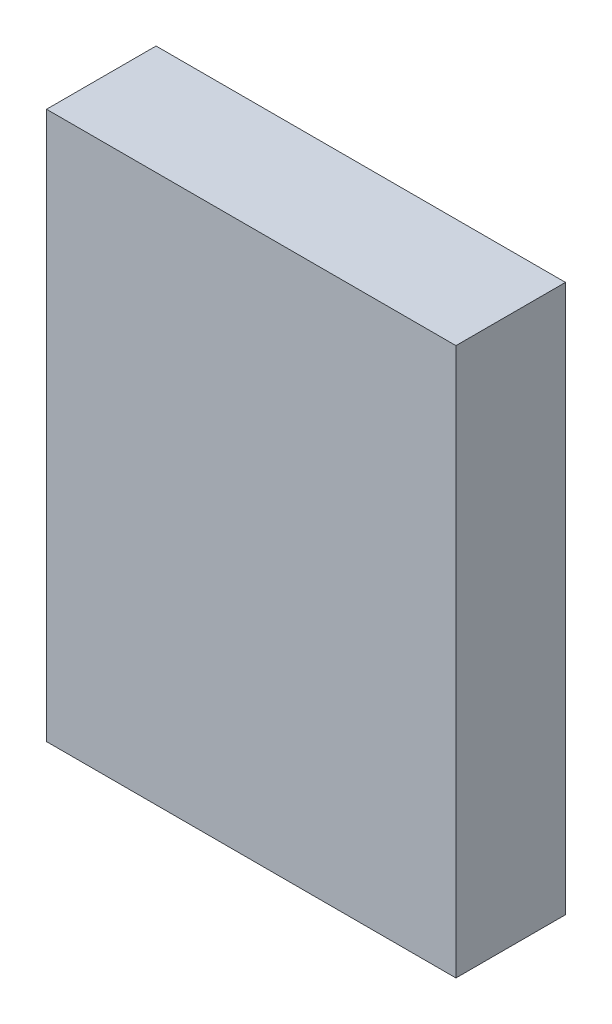
SolidWorks part; units mm, degrees
ref_plane "Спереди" through (0, 0, 0) normal (0, 0, 1) x (1, 0, 0)
ref_plane "Сверху" through (0, 0, 0) normal (0, 1, 0) x (1, 0, 0)
ref_plane "Справа" through (0, 0, 0) normal (1, 0, 0) x (0, 0, -1)
sketch "Эскиз5" plane through (0, 0, 0) normal (0, 0, 1) x (1, 0, 0)
  line L1 (-18.689, -25) -> (18.689, -25)
  line L2 (-18.689, -25) -> (-18.689, 25)
  line L3 (-18.689, 25) -> (18.689, 25)
  line L4 (18.689, -25) -> (18.689, 25)
  line L5 (-18.689, -25) -> (18.689, 25) construction
  line L6 (-18.689, 25) -> (18.689, -25) construction
  point P0 (0, 0)
extrude "Бобышка-Вытянуть2" add sketch "Эскиз5" along normal blind 10 contours L2 L3 L4 L1
sketch "ангренажный мост" plane through (0, 0, 10) normal (0, 0, 1) x (1, 0, 0)
  line L0 (-7.8996, -16.334) -> (-3.787, -11.9127)
  line L1 (1.1069, -9.3047) -> (3.4546, -11.6681)
  line L2 (3.9401, -11.9208) -> (8.2701, -12.6678)
  line L3 (9.4343, -11.4735) -> (9.7159, -10.401)
  line L4 (10.2173, -9.77) -> (11.3033, -9.1983)
  line L5 (11.6059, -14.0549) -> (8.4903, -14.3541)
  line L6 (8.3946, -14.3053) -> (-2.7438, -15.3749)
  line L7 (-2.7438, -15.3749) -> (-5.959, -18.794)
  line L8 (-5.9854, -20.5913) -> (-5.6833, -22.7215)
  line L9 (-5.8831, -23.4496) -> (-6.3288, -24.0048)
  line L10 (-11.3637, -19.8827) -> (-8.0539, -16.3245)
  line L11 (9.3569, -11.7683) -> (9.2937, -12.0094)
  line L12 (9.3569, -0.7683) -> (9.2937, -1.0094)
  line L13 (9.4343, -0.4735) -> (9.7159, 0.599)
  line L14 (10.2173, 1.23) -> (11.3033, 1.8017)
  line L15 (11.6059, -3.0549) -> (8.4903, -3.3541)
  line L16 (8.3946, -3.3053) -> (-2.7438, -4.3749)
  line L17 (-2.7438, -4.3749) -> (-5.959, -7.794)
  line L18 (-5.9854, -9.5913) -> (-5.6833, -11.7215)
  line L19 (-5.8831, -12.4496) -> (-6.3288, -13.0048)
  line L20 (-11.3637, -8.8827) -> (-8.0539, -5.3245)
  line L21 (-7.8996, -5.334) -> (-3.787, -0.9127)
  line L22 (1.1069, 1.6953) -> (3.4546, -0.6681)
  line L23 (3.9401, -0.9208) -> (8.2701, -1.6678)
  line L24 (9.3569, 10.2317) -> (9.2937, 9.9906)
  line L25 (9.4343, 10.5265) -> (9.7159, 11.599)
  line L26 (10.2173, 12.23) -> (11.3033, 12.8017)
  line L27 (11.6059, 7.9451) -> (8.4903, 7.6459)
  line L28 (8.3946, 7.6947) -> (-2.7438, 6.6251)
  line L29 (-2.7438, 6.6251) -> (-5.959, 3.206)
  line L30 (-5.9854, 1.4087) -> (-5.6833, -0.7215)
  line L31 (-5.8831, -1.4496) -> (-6.3288, -2.0048)
  line L32 (-11.3637, 2.1173) -> (-8.0539, 5.6755)
  line L33 (-7.8996, 5.666) -> (-3.787, 10.0873)
  line L34 (1.1069, 12.6953) -> (3.4546, 10.3319)
  line L35 (3.9401, 10.0792) -> (8.2701, 9.3322)
  line L36 (9.3569, 21.2317) -> (9.2937, 20.9906)
  line L37 (9.4343, 21.5265) -> (9.7159, 22.599)
  line L38 (10.2173, 23.23) -> (11.3033, 23.8017)
  line L39 (11.6059, 18.9451) -> (8.4903, 18.6459)
  line L40 (8.3946, 18.6947) -> (-2.7438, 17.6251)
  line L41 (-2.7438, 17.6251) -> (-5.959, 14.206)
  line L42 (-5.9854, 12.4087) -> (-5.6833, 10.2785)
  line L43 (-5.8831, 9.5504) -> (-6.3288, 8.9952)
  line L44 (-11.3637, 13.1173) -> (-8.0539, 16.6755)
  line L45 (-7.8996, 16.666) -> (-3.787, 21.0873)
  line L46 (1.1069, 23.6953) -> (3.4546, 21.3319)
  line L47 (3.9401, 21.0792) -> (8.2701, 20.3322)
  arc A17 (-11.3637, -19.8827) -> (-9.4971, -21.9436) centre (-1.0368, -12.4049) ccw
  arc A18 (-8.0539, -16.3245) -> (-7.8996, -16.334) centre (-7.9728, -16.2659) ccw
  arc A19 (-3.787, -11.9127) -> (-1.6906, -11.5403) centre (-3.7358, -6.1129) ccw
  arc A20 (9.1133, -1.3586) -> (9.2937, -1.0094) centre (8.4232, -0.7809) ccw
  arc A21 (-1.2128, -11.3353) -> (1.1069, -9.3047) centre (-3.7358, -6.1129) ccw
  arc A22 (3.4546, -11.6681) -> (3.9401, -11.9208) centre (4.0932, -11.0339) ccw
  arc A23 (8.2701, -12.6678) -> (8.9443, -12.5146) centre (8.4232, -11.7809) ccw
  arc A24 (10.2173, 1.23) -> (9.7159, 0.599) centre (10.6832, 0.3451) ccw
  arc A25 (10.2173, -9.77) -> (9.7159, -10.401) centre (10.6832, -10.6549) ccw
  arc A26 (11.6059, -14.0549) -> (11.3033, -9.1983) centre (-1.0368, -12.4049) ccw
  arc A27 (8.4903, -14.3541) -> (8.3946, -14.3053) centre (8.4042, -14.4049) ccw
  arc A28 (-5.959, -18.794) -> (-5.9854, -20.5913) centre (-0.2428, -19.7769) ccw
  arc A29 (-5.8831, -23.4496) -> (-5.6833, -22.7215) centre (-6.6238, -22.8549) ccw
  arc A30 (-8.0552, -23.0493) -> (-6.3288, -24.0048) centre (-1.0368, -12.4049) ccw
  arc A31 (-8.0552, -23.0493) -> (-9.4971, -21.9436) centre (-8.5218, -22.1649) ccw
  arc A44 (11.6059, -3.0549) -> (11.3033, 1.8017) centre (-1.0368, -1.4049) ccw
  arc A51 (9.1133, -12.3586) -> (9.2937, -12.0094) centre (8.4232, -11.7809) ccw
  arc A52 (8.4903, -3.3541) -> (8.3946, -3.3053) centre (8.4042, -3.4049) ccw
  arc A53 (-5.959, -7.794) -> (-5.9854, -9.5913) centre (-0.2428, -8.7769) ccw
  arc A54 (-5.8831, -12.4496) -> (-5.6833, -11.7215) centre (-6.6238, -11.8549) ccw
  arc A55 (-8.0552, -12.0493) -> (-6.3288, -13.0048) centre (-1.0368, -1.4049) ccw
  arc A56 (-8.0552, -12.0493) -> (-9.4971, -10.9436) centre (-8.5218, -11.1649) ccw
  arc A57 (-11.3637, -8.8827) -> (-9.4971, -10.9436) centre (-1.0368, -1.4049) ccw
  arc A58 (-8.0539, -5.3245) -> (-7.8996, -5.334) centre (-7.9728, -5.2659) ccw
  arc A59 (-3.787, -0.9127) -> (-1.6906, -0.5403) centre (-3.7358, 4.8871) ccw
  arc A60 (-1.2128, -0.3353) -> (1.1069, 1.6953) centre (-3.7358, 4.8871) ccw
  arc A61 (3.4546, -0.6681) -> (3.9401, -0.9208) centre (4.0932, -0.0339) ccw
  arc A62 (8.2701, -1.6678) -> (8.9443, -1.5146) centre (8.4232, -0.7809) ccw
  arc A63 (9.1133, 9.6414) -> (9.2937, 9.9906) centre (8.4232, 10.2191) ccw
  arc A64 (10.2173, 12.23) -> (9.7159, 11.599) centre (10.6832, 11.3451) ccw
  arc A65 (11.6059, 7.9451) -> (11.3033, 12.8017) centre (-1.0368, 9.5951) ccw
  arc A66 (8.4903, 7.6459) -> (8.3946, 7.6947) centre (8.4042, 7.5951) ccw
  arc A67 (-5.959, 3.206) -> (-5.9854, 1.4087) centre (-0.2428, 2.2231) ccw
  arc A68 (-5.8831, -1.4496) -> (-5.6833, -0.7215) centre (-6.6238, -0.8549) ccw
  arc A69 (-8.0552, -1.0493) -> (-6.3288, -2.0048) centre (-1.0368, 9.5951) ccw
  arc A70 (-8.0552, -1.0493) -> (-9.4971, 0.0564) centre (-8.5218, -0.1649) ccw
  arc A71 (-11.3637, 2.1173) -> (-9.4971, 0.0564) centre (-1.0368, 9.5951) ccw
  arc A72 (-8.0539, 5.6755) -> (-7.8996, 5.666) centre (-7.9728, 5.7341) ccw
  arc A73 (-3.787, 10.0873) -> (-1.6906, 10.4597) centre (-3.7358, 15.8871) ccw
  arc A74 (-1.2128, 10.6647) -> (1.1069, 12.6953) centre (-3.7358, 15.8871) ccw
  arc A75 (3.4546, 10.3319) -> (3.9401, 10.0792) centre (4.0932, 10.9661) ccw
  arc A76 (8.2701, 9.3322) -> (8.9443, 9.4854) centre (8.4232, 10.2191) ccw
  arc A77 (9.1133, 20.6414) -> (9.2937, 20.9906) centre (8.4232, 21.2191) ccw
  arc A78 (10.2173, 23.23) -> (9.7159, 22.599) centre (10.6832, 22.3451) ccw
  arc A79 (11.6059, 18.9451) -> (11.3033, 23.8017) centre (-1.0368, 20.5951) ccw
  arc A80 (8.4903, 18.6459) -> (8.3946, 18.6947) centre (8.4042, 18.5951) ccw
  arc A81 (-5.959, 14.206) -> (-5.9854, 12.4087) centre (-0.2428, 13.2231) ccw
  arc A82 (-5.8831, 9.5504) -> (-5.6833, 10.2785) centre (-6.6238, 10.1451) ccw
  arc A83 (-8.0552, 9.9507) -> (-6.3288, 8.9952) centre (-1.0368, 20.5951) ccw
  arc A84 (-8.0552, 9.9507) -> (-9.4971, 11.0564) centre (-8.5218, 10.8351) ccw
  arc A85 (-11.3637, 13.1173) -> (-9.4971, 11.0564) centre (-1.0368, 20.5951) ccw
  arc A86 (-8.0539, 16.6755) -> (-7.8996, 16.666) centre (-7.9728, 16.7341) ccw
  arc A87 (-3.787, 21.0873) -> (-1.6906, 21.4597) centre (-3.7358, 26.8871) ccw
  arc A88 (-1.2128, 21.6647) -> (1.1069, 23.6953) centre (-3.7358, 26.8871) ccw
  arc A89 (3.4546, 21.3319) -> (3.9401, 21.0792) centre (4.0932, 21.9661) ccw
  arc A90 (8.2701, 20.3322) -> (8.9443, 20.4854) centre (8.4232, 21.2191) ccw
  spline S0 degree 3 poles (9.4343, -0.4735) (9.4089, -0.5703) (9.3832, -0.6682) (9.3569, -0.7683) knots 0 0 0 0 1 1 1 1
  spline S1 degree 3 poles (-1.6906, -11.5403) (-1.6123, -11.5108) (-1.5305, -11.478) (-1.3682, -11.4084) (-1.2881, -11.3718) (-1.2128, -11.3353) knots 0 0 0 0 0.5 0.5 1 1 1 1
  spline S2 degree 3 poles (-1.6906, -0.5403) (-1.6123, -0.5108) (-1.5305, -0.478) (-1.3682, -0.4084) (-1.2881, -0.3718) (-1.2128, -0.3353) knots 0 0 0 0 0.5 0.5 1 1 1 1
  spline S3 degree 3 poles (9.1133, -1.3586) (9.0621, -1.4197) (9.0057, -1.471) (8.9443, -1.5146) knots 0 0 0 0 1 1 1 1
  spline S4 degree 3 poles (9.4343, 10.5265) (9.4089, 10.4297) (9.3832, 10.3318) (9.3569, 10.2317) knots 0 0 0 0 1 1 1 1
  spline S5 degree 3 poles (9.4343, -11.4735) (9.4089, -11.5703) (9.3832, -11.6682) (9.3569, -11.7683) knots 0 0 0 0 1 1 1 1
  spline S6 degree 3 poles (9.1133, -12.3586) (9.0621, -12.4197) (9.0057, -12.471) (8.9443, -12.5146) knots 0 0 0 0 1 1 1 1
  spline S7 degree 3 poles (-1.6906, 10.4597) (-1.6123, 10.4892) (-1.5305, 10.522) (-1.3682, 10.5916) (-1.2881, 10.6282) (-1.2128, 10.6647) knots 0 0 0 0 0.5 0.5 1 1 1 1
  spline S8 degree 3 poles (9.1133, 9.6414) (9.0621, 9.5803) (9.0057, 9.529) (8.9443, 9.4854) knots 0 0 0 0 1 1 1 1
  spline S9 degree 3 poles (9.4343, 21.5265) (9.4089, 21.4297) (9.3832, 21.3318) (9.3569, 21.2317) knots 0 0 0 0 1 1 1 1
  spline S10 degree 3 poles (-1.6906, 21.4597) (-1.6123, 21.4892) (-1.5305, 21.522) (-1.3682, 21.5916) (-1.2881, 21.6282) (-1.2128, 21.6647) knots 0 0 0 0 0.5 0.5 1 1 1 1
  spline S11 degree 3 poles (9.1133, 20.6414) (9.0621, 20.5803) (9.0057, 20.529) (8.9443, 20.4854) knots 0 0 0 0 1 1 1 1
  dimension "D1" = 4
sketch "под штифты и углы" plane through (0, 0, 10) normal (0, 0, 1) x (1, 0, 0)
  circle A0 centre (10.6832, -10.6549) radius 1
  circle A1 centre (-6.6238, -22.8549) radius 1
  circle A4 centre (-9.4971, -21.9436) radius 1
  circle A5 centre (-8.0552, -23.0493) radius 1
  circle A6 centre (9.7735, -9.5605) radius 1
  circle A7 centre (11.0975, -8.9025) radius 1
  circle A8 centre (11.8685, -14.5114) radius 1
  circle A9 centre (9.7735, 1.4395) radius 1
  circle A10 centre (11.0975, 2.0975) radius 1
  circle A11 centre (10.6832, 0.3451) radius 1
  circle A12 centre (11.8685, -3.5114) radius 1
  circle A13 centre (-9.4971, -10.9436) radius 1
  circle A14 centre (-8.0552, -12.0493) radius 1
  circle A15 centre (-6.6238, -11.8549) radius 1
  circle A16 centre (9.7735, 12.4395) radius 1
  circle A17 centre (11.0975, 13.0975) radius 1
  circle A18 centre (10.6832, 11.3451) radius 1
  circle A19 centre (11.8685, 7.4886) radius 1
  circle A20 centre (-9.4971, 0.0564) radius 1
  circle A21 centre (-8.0552, -1.0493) radius 1
  circle A22 centre (-6.6238, -0.8549) radius 1
  circle A23 centre (9.7735, 23.4395) radius 1
  circle A24 centre (11.0975, 24.0975) radius 1
  circle A25 centre (10.6832, 22.3451) radius 1
  circle A26 centre (11.8685, 18.4886) radius 1
  circle A27 centre (-9.4971, 11.0564) radius 1
  circle A28 centre (-8.0552, 9.9507) radius 1
  circle A29 centre (-6.6238, 10.1451) radius 1
  dimension "D1" = 4
sketch "сЪем" plane through (0, 0, 10) normal (0, 0, 1) x (1, 0, 0)
  line L0 (0, -32.2096) -> (0, 32.2096) construction
  line L1 (-1, -32.2096) -> (-1, 32.2096)
  line L2 (1, -32.2096) -> (1, 32.2096)
  arc A0 (-1, -32.2096) -> (1, -32.2096) centre (0, -32.2096) ccw
  arc A1 (1, 32.2096) -> (-1, 32.2096) centre (0, 32.2096) ccw
  point P2 (0, 0)
sketch "перлаж" plane through (0, 0, 10) normal (0, 0, 1) x (1, 0, 0)
  circle A0 centre (-10.5945, -20.0559) radius 1
  circle A1 centre (-9.4734, -20.898) radius 1
  circle A3 centre (-7.2312, -22.5823) radius 1
  circle A4 centre (-6.1101, -23.4244) radius 1
  circle A11 centre (-7.464, -20.763) radius 1
  circle A12 centre (-6.3429, -21.6052) radius 1
  circle A19 centre (-7.6968, -18.9438) radius 1
  circle A20 centre (-6.5757, -19.7859) radius 1
  circle A28 centre (-6.8085, -17.9666) radius 1
  circle A29 centre (-5.6874, -18.8088) radius 1
  circle A37 centre (-5.9202, -16.9895) radius 1
  circle A38 centre (-4.799, -17.8316) radius 1
  circle A46 centre (-5.0318, -16.0124) radius 1
  circle A47 centre (-3.9107, -16.8545) radius 1
  circle A55 centre (-4.1435, -15.0352) radius 1
  circle A56 centre (-3.0224, -15.8774) radius 1
  circle A64 centre (-3.2552, -14.0581) radius 1
  circle A65 centre (-2.1341, -14.9002) radius 1
  circle A73 centre (-2.3669, -13.081) radius 1
  circle A74 centre (-1.2458, -13.9231) radius 1
  circle A75 centre (-0.1247, -14.7652) radius 1
  circle A82 centre (-1.4786, -12.1038) radius 1
  circle A83 centre (-0.3575, -12.946) radius 1
  circle A84 centre (0.7636, -13.7881) radius 1
  circle A85 centre (1.8847, -14.6302) radius 1
  circle A91 centre (-0.5903, -11.1267) radius 1
  circle A92 centre (0.5308, -11.9688) radius 1
  circle A93 centre (1.6519, -12.8109) radius 1
  circle A94 centre (2.7731, -13.6531) radius 1
  circle A95 centre (3.8942, -14.4952) radius 1
  circle A101 centre (1.4191, -10.9917) radius 1
  circle A102 centre (2.5403, -11.8338) radius 1
  circle A103 centre (3.6614, -12.6759) radius 1
  circle A104 centre (4.7825, -13.5181) radius 1
  circle A105 centre (5.9036, -14.3602) radius 1
  circle A112 centre (4.5497, -11.6988) radius 1
  circle A113 centre (5.6708, -12.5409) radius 1
  circle A114 centre (6.7919, -13.383) radius 1
  circle A115 centre (7.913, -14.2252) radius 1
  circle A123 centre (7.6802, -12.4059) radius 1
  circle A124 centre (8.8013, -13.248) radius 1
  circle A125 centre (9.9224, -14.0902) radius 1
  circle A143 centre (11.6991, -12.1359) radius 1
  circle A151 centre (11.4663, -10.3166) radius 1
  circle A163 centre (-9.7062, -19.0788) radius 1
  circle A164 centre (-8.8179, -18.1017) radius 1
  circle A165 centre (-7.9296, -17.1245) radius 1
  circle A166 centre (-7.0413, -16.1474) radius 1
  circle A167 centre (-6.153, -15.1703) radius 1
  circle A168 centre (-5.2646, -14.1931) radius 1
  circle A169 centre (-4.3763, -13.216) radius 1
  circle A170 centre (-3.488, -12.2389) radius 1
  circle A171 centre (-2.5997, -11.2617) radius 1
  circle A180 centre (-4.9889, -24.2665) radius 1
  circle A181 centre (-3.8678, -25.1087) radius 1
  circle A182 centre (-2.7467, -25.9508) radius 1
  circle A183 centre (-1.6256, -26.7929) radius 1
  circle A184 centre (-0.5045, -27.635) radius 1
  circle A185 centre (-4.1006, -23.2894) radius 1
  circle A186 centre (-2.9795, -24.1315) radius 1
  circle A187 centre (-1.8584, -24.9736) radius 1
  circle A188 centre (-0.7373, -25.8158) radius 1
  circle A189 centre (0.3838, -26.6579) radius 1
  circle A190 centre (-3.2123, -22.3123) radius 1
  circle A191 centre (-2.0912, -23.1544) radius 1
  circle A192 centre (-0.9701, -23.9965) radius 1
  circle A193 centre (0.151, -24.8386) radius 1
  circle A194 centre (1.2721, -25.6807) radius 1
  circle A195 centre (-3.4451, -20.493) radius 1
  circle A196 centre (-2.324, -21.3351) radius 1
  circle A197 centre (-1.2029, -22.1773) radius 1
  circle A198 centre (-0.0818, -23.0194) radius 1
  circle A199 centre (1.0393, -23.8615) radius 1
  circle A200 centre (2.1604, -24.7036) radius 1
  circle A201 centre (-0.3146, -21.2001) radius 1
  circle A202 centre (0.8065, -22.0422) radius 1
  circle A203 centre (1.9276, -22.8844) radius 1
  circle A204 centre (3.0487, -23.7265) radius 1
  circle A205 centre (1.6948, -21.0651) radius 1
  circle A206 centre (2.8159, -21.9072) radius 1
  circle A207 centre (3.9371, -22.7493) radius 1
  circle A208 centre (3.7043, -20.9301) radius 1
  circle A209 centre (-4.5662, -19.6509) radius 1
  circle A210 centre (-4.3334, -21.4701) radius 1
  circle A211 centre (0.5737, -20.223) radius 1
  circle A212 centre (0.3409, -18.4037) radius 1
  circle A213 centre (1.462, -19.2458) radius 1
  circle A214 centre (2.5831, -20.088) radius 1
  circle A215 centre (4.8254, -21.7722) radius 1
  circle A216 centre (0.1081, -16.5845) radius 1
  circle A217 centre (1.2292, -17.4266) radius 1
  circle A218 centre (2.3503, -18.2687) radius 1
  circle A219 centre (3.4715, -19.1108) radius 1
  circle A220 centre (4.5926, -19.953) radius 1
  circle A221 centre (5.7137, -20.7951) radius 1
  circle A222 centre (2.1175, -16.4495) radius 1
  circle A223 centre (3.2387, -17.2916) radius 1
  circle A224 centre (4.3598, -18.1337) radius 1
  circle A225 centre (5.4809, -18.9758) radius 1
  circle A226 centre (6.602, -19.8179) radius 1
  circle A227 centre (4.127, -16.3144) radius 1
  circle A228 centre (5.2481, -17.1566) radius 1
  circle A229 centre (6.3692, -17.9987) radius 1
  circle A230 centre (7.4903, -18.8408) radius 1
  circle A231 centre (6.1364, -16.1794) radius 1
  circle A232 centre (7.2575, -17.0216) radius 1
  circle A233 centre (8.3786, -17.8637) radius 1
  circle A234 centre (-3.6779, -18.6738) radius 1
  circle A235 centre (-2.5568, -19.5159) radius 1
  circle A236 centre (-1.4357, -20.358) radius 1
  circle A237 centre (-2.7896, -17.6966) radius 1
  circle A238 centre (-1.6685, -18.5387) radius 1
  circle A239 centre (-0.5474, -19.3809) radius 1
  circle A240 centre (-1.9013, -16.7195) radius 1
  circle A241 centre (-0.7802, -17.5616) radius 1
  circle A242 centre (8.1458, -16.0444) radius 1
  circle A243 centre (10.1552, -15.9094) radius 1
  circle A244 centre (9.2669, -16.8865) radius 1
  circle A245 centre (13.4757, -10.1816) radius 1
  circle A246 centre (13.7085, -12.0009) radius 1
  circle A247 centre (14.5968, -11.0237) radius 1
  circle A248 centre (3.8513, -6.241) radius 1
  circle A249 centre (4.7396, -5.2639) radius 1
  circle A250 centre (5.8607, -6.106) radius 1
  circle A251 centre (5.6279, -4.2868) radius 1
  circle A252 centre (6.749, -5.1289) radius 1
  circle A253 centre (7.8701, -5.971) radius 1
  circle A254 centre (2.7302, -5.3989) radius 1
  circle A255 centre (3.6185, -4.4218) radius 1
  circle A256 centre (4.5068, -3.4446) radius 1
  circle A257 centre (2.963, -7.2182) radius 1
  circle A258 centre (4.9724, -7.0832) radius 1
  circle A259 centre (6.9818, -6.9481) radius 1
  circle A260 centre (8.1029, -7.7903) radius 1
  circle A261 centre (8.9912, -6.8131) radius 1
  circle A262 centre (10.1124, -7.6552) radius 1
  circle A263 centre (0.9535, -7.3532) radius 1
  circle A264 centre (1.8419, -6.376) radius 1
  circle A265 centre (0.0652, -8.3303) radius 1
  circle A266 centre (2.0747, -8.1953) radius 1
  circle A267 centre (4.0841, -8.0603) radius 1
  circle A268 centre (6.0935, -7.9253) radius 1
  circle A269 centre (-0.8231, -9.3074) radius 1
  circle A270 centre (-1.7114, -10.2846) radius 1
  circle A271 centre (3.1958, -9.0374) radius 1
  circle A272 centre (4.3169, -9.8795) radius 1
  circle A273 centre (5.2052, -8.9024) radius 1
  circle A274 centre (7.2146, -8.7674) radius 1
  circle A275 centre (9.224, -8.6324) radius 1
  circle A276 centre (11.2335, -8.4974) radius 1
  circle A277 centre (5.438, -10.7217) radius 1
  circle A278 centre (6.3263, -9.7445) radius 1
  circle A279 centre (8.3357, -9.6095) radius 1
  circle A280 centre (7.4474, -10.5867) radius 1
  circle A281 centre (6.5591, -11.5638) radius 1
  circle A282 centre (8.5685, -11.4288) radius 1
  circle A283 centre (9.6896, -12.2709) radius 1
  circle A284 centre (-8.5851, -19.9209) radius 1
  circle A285 centre (11.9319, -13.9551) radius 1
  circle A286 centre (10.3452, -9.4745) radius 1
  circle A287 centre (12.3546, -9.3395) radius 1
  circle A288 centre (9.4568, -10.4516) radius 1
  circle A289 centre (-8.3523, -21.7402) radius 1
  circle A290 centre (0.9964, -15.6073) radius 1
  circle A291 centre (3.0059, -15.4723) radius 1
  circle A292 centre (5.0153, -15.3373) radius 1
  circle A293 centre (7.0247, -15.2023) radius 1
  circle A294 centre (9.0341, -15.0673) radius 1
  circle A295 centre (11.0436, -14.9323) radius 1
  circle A296 centre (12.5874, -11.1587) radius 1
  circle A297 centre (12.8202, -12.978) radius 1
  circle A298 centre (10.8108, -13.113) radius 1
  circle A299 centre (11.1199, -13.3961) radius 1
  circle A300 centre (10.578, -11.2938) radius 1
  circle A301 centre (10.0957, -10.635) radius 1
  circle A302 centre (1.1863, -9.1724) radius 1
  circle A303 centre (2.3075, -10.0146) radius 1
  circle A304 centre (3.4286, -10.8567) radius 1
  circle A305 centre (0.298, -10.1496) radius 1
  circle A306 centre (0.7998, -9.9463) radius 1
  circle A307 centre (-5.2217, -22.4473) radius 1
  circle A308 centre (-5.4545, -20.628) radius 1
  circle A309 centre (-1.013, -15.7424) radius 1
  circle A310 centre (-10.5945, -9.0559) radius 1
  circle A311 centre (-9.4734, -9.898) radius 1
  circle A312 centre (-7.2312, -11.5823) radius 1
  circle A313 centre (-6.1101, -12.4244) radius 1
  circle A314 centre (-7.464, -9.763) radius 1
  circle A315 centre (-6.3429, -10.6052) radius 1
  circle A316 centre (-7.6968, -7.9438) radius 1
  circle A317 centre (-6.5757, -8.7859) radius 1
  circle A318 centre (-6.8085, -6.9666) radius 1
  circle A319 centre (-5.6874, -7.8088) radius 1
  circle A320 centre (-5.9202, -5.9895) radius 1
  circle A321 centre (-4.799, -6.8316) radius 1
  circle A322 centre (-5.0318, -5.0124) radius 1
  circle A323 centre (-3.9107, -5.8545) radius 1
  circle A324 centre (-4.1435, -4.0352) radius 1
  circle A325 centre (-3.0224, -4.8774) radius 1
  circle A326 centre (-3.2552, -3.0581) radius 1
  circle A327 centre (-2.1341, -3.9002) radius 1
  circle A328 centre (-2.3669, -2.081) radius 1
  circle A329 centre (-1.2458, -2.9231) radius 1
  circle A330 centre (-0.1247, -3.7652) radius 1
  circle A331 centre (-1.4786, -1.1038) radius 1
  circle A332 centre (-0.3575, -1.946) radius 1
  circle A333 centre (0.7636, -2.7881) radius 1
  circle A334 centre (1.8847, -3.6302) radius 1
  circle A335 centre (-0.5903, -0.1267) radius 1
  circle A336 centre (0.5308, -0.9688) radius 1
  circle A337 centre (1.6519, -1.8109) radius 1
  circle A338 centre (2.7731, -2.6531) radius 1
  circle A339 centre (3.8942, -3.4952) radius 1
  circle A340 centre (1.4191, 0.0083) radius 1
  circle A341 centre (2.5403, -0.8338) radius 1
  circle A342 centre (3.6614, -1.6759) radius 1
  circle A343 centre (4.7825, -2.5181) radius 1
  circle A344 centre (5.9036, -3.3602) radius 1
  circle A345 centre (4.5497, -0.6988) radius 1
  circle A346 centre (5.6708, -1.5409) radius 1
  circle A347 centre (6.7919, -2.383) radius 1
  circle A348 centre (7.913, -3.2252) radius 1
  circle A349 centre (7.6802, -1.4059) radius 1
  circle A350 centre (8.8013, -2.248) radius 1
  circle A351 centre (9.9224, -3.0902) radius 1
  circle A352 centre (11.6991, -1.1359) radius 1
  circle A353 centre (11.4663, 0.6834) radius 1
  circle A354 centre (-9.7062, -8.0788) radius 1
  circle A355 centre (-8.8179, -7.1017) radius 1
  circle A356 centre (-7.9296, -6.1245) radius 1
  circle A357 centre (-7.0413, -5.1474) radius 1
  circle A358 centre (-6.153, -4.1703) radius 1
  circle A359 centre (-5.2646, -3.1931) radius 1
  circle A360 centre (-4.3763, -2.216) radius 1
  circle A361 centre (-3.488, -1.2389) radius 1
  circle A362 centre (-2.5997, -0.2617) radius 1
  circle A363 centre (11.1199, -2.3961) radius 1
  circle A364 centre (10.0957, 0.365) radius 1
  circle A365 centre (0.7998, 1.0537) radius 1
  circle A366 centre (-10.5945, 1.9441) radius 1
  circle A367 centre (-9.4734, 1.102) radius 1
  circle A368 centre (-7.2312, -0.5823) radius 1
  circle A369 centre (-6.1101, -1.4244) radius 1
  circle A370 centre (-7.464, 1.237) radius 1
  circle A371 centre (-6.3429, 0.3948) radius 1
  circle A372 centre (-7.6968, 3.0562) radius 1
  circle A373 centre (-6.5757, 2.2141) radius 1
  circle A374 centre (-6.8085, 4.0334) radius 1
  circle A375 centre (-5.6874, 3.1912) radius 1
  circle A376 centre (-5.9202, 5.0105) radius 1
  circle A377 centre (-4.799, 4.1684) radius 1
  circle A378 centre (-5.0318, 5.9876) radius 1
  circle A379 centre (-3.9107, 5.1455) radius 1
  circle A380 centre (-4.1435, 6.9648) radius 1
  circle A381 centre (-3.0224, 6.1226) radius 1
  circle A382 centre (-3.2552, 7.9419) radius 1
  circle A383 centre (-2.1341, 7.0998) radius 1
  circle A384 centre (-2.3669, 8.919) radius 1
  circle A385 centre (-1.2458, 8.0769) radius 1
  circle A386 centre (-0.1247, 7.2348) radius 1
  circle A387 centre (-1.4786, 9.8962) radius 1
  circle A388 centre (-0.3575, 9.054) radius 1
  circle A389 centre (0.7636, 8.2119) radius 1
  circle A390 centre (1.8847, 7.3698) radius 1
  circle A391 centre (-0.5903, 10.8733) radius 1
  circle A392 centre (0.5308, 10.0312) radius 1
  circle A393 centre (1.6519, 9.1891) radius 1
  circle A394 centre (2.7731, 8.3469) radius 1
  circle A395 centre (3.8942, 7.5048) radius 1
  circle A396 centre (1.4191, 11.0083) radius 1
  circle A397 centre (2.5403, 10.1662) radius 1
  circle A398 centre (3.6614, 9.3241) radius 1
  circle A399 centre (4.7825, 8.4819) radius 1
  circle A400 centre (5.9036, 7.6398) radius 1
  circle A401 centre (4.5497, 10.3012) radius 1
  circle A402 centre (5.6708, 9.4591) radius 1
  circle A403 centre (6.7919, 8.617) radius 1
  circle A404 centre (7.913, 7.7748) radius 1
  circle A405 centre (7.6802, 9.5941) radius 1
  circle A406 centre (8.8013, 8.752) radius 1
  circle A407 centre (9.9224, 7.9098) radius 1
  circle A408 centre (11.6991, 9.8641) radius 1
  circle A409 centre (11.4663, 11.6834) radius 1
  circle A410 centre (-9.7062, 2.9212) radius 1
  circle A411 centre (-8.8179, 3.8983) radius 1
  circle A412 centre (-7.9296, 4.8755) radius 1
  circle A413 centre (-7.0413, 5.8526) radius 1
  circle A414 centre (-6.153, 6.8297) radius 1
  circle A415 centre (-5.2646, 7.8069) radius 1
  circle A416 centre (-4.3763, 8.784) radius 1
  circle A417 centre (-3.488, 9.7611) radius 1
  circle A418 centre (-2.5997, 10.7383) radius 1
  circle A419 centre (11.1199, 8.6039) radius 1
  circle A420 centre (10.0957, 11.365) radius 1
  circle A421 centre (0.7998, 12.0537) radius 1
  circle A422 centre (-10.5945, 12.9441) radius 1
  circle A423 centre (-9.4734, 12.102) radius 1
  circle A424 centre (-7.2312, 10.4177) radius 1
  circle A425 centre (-6.1101, 9.5756) radius 1
  circle A426 centre (-7.464, 12.237) radius 1
  circle A427 centre (-6.3429, 11.3948) radius 1
  circle A428 centre (-7.6968, 14.0562) radius 1
  circle A429 centre (-6.5757, 13.2141) radius 1
  circle A430 centre (-6.8085, 15.0334) radius 1
  circle A431 centre (-5.6874, 14.1912) radius 1
  circle A432 centre (-5.9202, 16.0105) radius 1
  circle A433 centre (-4.799, 15.1684) radius 1
  circle A434 centre (-5.0318, 16.9876) radius 1
  circle A435 centre (-3.9107, 16.1455) radius 1
  circle A436 centre (-4.1435, 17.9648) radius 1
  circle A437 centre (-3.0224, 17.1226) radius 1
  circle A438 centre (-3.2552, 18.9419) radius 1
  circle A439 centre (-2.1341, 18.0998) radius 1
  circle A440 centre (-2.3669, 19.919) radius 1
  circle A441 centre (-1.2458, 19.0769) radius 1
  circle A442 centre (-0.1247, 18.2348) radius 1
  circle A443 centre (-1.4786, 20.8962) radius 1
  circle A444 centre (-0.3575, 20.054) radius 1
  circle A445 centre (0.7636, 19.2119) radius 1
  circle A446 centre (1.8847, 18.3698) radius 1
  circle A447 centre (-0.5903, 21.8733) radius 1
  circle A448 centre (0.5308, 21.0312) radius 1
  circle A449 centre (1.6519, 20.1891) radius 1
  circle A450 centre (2.7731, 19.3469) radius 1
  circle A451 centre (3.8942, 18.5048) radius 1
  circle A452 centre (1.4191, 22.0083) radius 1
  circle A453 centre (2.5403, 21.1662) radius 1
  circle A454 centre (3.6614, 20.3241) radius 1
  circle A455 centre (4.7825, 19.4819) radius 1
  circle A456 centre (5.9036, 18.6398) radius 1
  circle A457 centre (4.5497, 21.3012) radius 1
  circle A458 centre (5.6708, 20.4591) radius 1
  circle A459 centre (6.7919, 19.617) radius 1
  circle A460 centre (7.913, 18.7748) radius 1
  circle A461 centre (7.6802, 20.5941) radius 1
  circle A462 centre (8.8013, 19.752) radius 1
  circle A463 centre (9.9224, 18.9098) radius 1
  circle A464 centre (11.6991, 20.8641) radius 1
  circle A465 centre (11.4663, 22.6834) radius 1
  circle A466 centre (-9.7062, 13.9212) radius 1
  circle A467 centre (-8.8179, 14.8983) radius 1
  circle A468 centre (-7.9296, 15.8755) radius 1
  circle A469 centre (-7.0413, 16.8526) radius 1
  circle A470 centre (-6.153, 17.8297) radius 1
  circle A471 centre (-5.2646, 18.8069) radius 1
  circle A472 centre (-4.3763, 19.784) radius 1
  circle A473 centre (-3.488, 20.7611) radius 1
  circle A474 centre (-2.5997, 21.7383) radius 1
  circle A475 centre (11.1199, 19.6039) radius 1
  circle A476 centre (10.0957, 22.365) radius 1
  circle A477 centre (0.7998, 23.0537) radius 1
  dimension "D1" = 10
  dimension "D2" = 18
  dimension "D3" = 4
sketch "мост с отверстиями" plane through (0, 0, 10) normal (0, 0, 1) x (1, 0, 0)
  line L0 (-7.8973, -16.3331) -> (-3.7847, -11.9118)
  line L1 (1.1093, -9.3038) -> (3.457, -11.6673)
  line L2 (3.9425, -11.9199) -> (8.2725, -12.6669)
  line L3 (9.4367, -11.4727) -> (9.7183, -10.4001)
  line L4 (10.2197, -9.7691) -> (11.3057, -9.1974)
  line L5 (11.6083, -14.054) -> (8.4926, -14.3532)
  line L6 (8.3969, -14.3045) -> (-2.7415, -15.374)
  line L7 (-2.7415, -15.374) -> (-5.9566, -18.7931)
  line L8 (-5.983, -20.5905) -> (-5.6809, -22.7206)
  line L9 (-5.8807, -23.4488) -> (-6.3264, -24.0039)
  line L10 (-11.3614, -19.8819) -> (-8.0515, -16.3236)
  line L11 (9.3593, -11.7675) -> (9.296, -12.0086)
  circle A0 centre (-8.6845, -18.404) radius 0.3625
  circle A1 centre (6.5655, -13.454) radius 0.33
  circle A2 centre (-4.8075, -15.436) radius 1.0839
  circle A3 centre (-9.0765, -20.054) radius 1.1232
  circle A4 centre (10.6855, -10.654) radius 0.4
  circle A5 centre (-6.6215, -22.854) radius 0.4
  circle A6 centre (3.8625, -13.142) radius 1.0839
  circle A7 centre (-7.1845, -18.004) radius 0.33
  circle A8 centre (7.9655, -13.604) radius 0.3625
  circle A9 centre (-4.8075, -15.436) radius 0.7731
  circle A10 centre (-4.8075, -15.436) radius 0.53
  circle A11 centre (-1.0345, -12.404) radius 0.7731
  circle A12 centre (-1.0345, -12.404) radius 0.53
  circle A13 centre (3.8625, -13.142) radius 0.7731
  circle A14 centre (3.8625, -13.142) radius 0.53
  circle A15 centre (-9.0765, -20.054) radius 0.45
  circle A16 centre (10.0645, -12.404) radius 0.45
  arc A17 (-11.3614, -19.8819) -> (-9.4947, -21.9427) centre (-1.0345, -12.404) ccw
  arc A18 (-8.0515, -16.3236) -> (-7.8973, -16.3331) centre (-7.9705, -16.265) ccw
  arc A19 (-3.7847, -11.9118) -> (-1.6882, -11.5394) centre (-3.7335, -6.112) ccw
  arc A20 (-1.6882, -11.5394) -> (-1.2104, -11.3345) centre (-1.0345, -12.404) ccw
  arc A21 (-1.2104, -11.3345) -> (1.1093, -9.3038) centre (-3.7335, -6.112) ccw
  arc A22 (3.457, -11.6673) -> (3.9425, -11.9199) centre (4.0955, -11.033) ccw
  arc A23 (8.2725, -12.6669) -> (8.9467, -12.5138) centre (8.4255, -11.78) ccw
  arc A24 (8.9467, -12.5138) -> (9.4367, -11.4727) centre (10.0645, -12.404) ccw
  arc A25 (10.2197, -9.7691) -> (9.7183, -10.4001) centre (10.6855, -10.654) ccw
  arc A26 (11.6083, -14.054) -> (11.3057, -9.1974) centre (-1.0345, -12.404) ccw
  arc A27 (8.4926, -14.3532) -> (8.3969, -14.3045) centre (8.4065, -14.404) ccw
  arc A28 (-5.9566, -18.7931) -> (-5.983, -20.5905) centre (-0.2405, -19.776) ccw
  arc A29 (-5.8807, -23.4488) -> (-5.6809, -22.7206) centre (-6.6215, -22.854) ccw
  arc A30 (-8.0529, -23.0485) -> (-6.3264, -24.0039) centre (-1.0345, -12.404) ccw
  arc A31 (-8.0529, -23.0485) -> (-9.4947, -21.9427) centre (-8.5195, -22.164) ccw
  arc A32 (-10.0265, -20.054) -> (-8.1265, -20.054) centre (-9.0765, -20.054) ccw
  arc A33 (-8.1265, -20.054) -> (-10.0265, -20.054) centre (-9.0765, -20.054) ccw
  arc A34 (-8.947, -18.404) -> (-8.422, -18.404) centre (-8.6845, -18.404) ccw
  arc A35 (-8.422, -18.404) -> (-8.947, -18.404) centre (-8.6845, -18.404) ccw
  arc A36 (-6.8845, -18.004) -> (-7.1845, -17.704) centre (-7.1845, -18.004) ccw
  arc A37 (-4.8075, -14.436) -> (-4.8075, -16.436) centre (-4.8075, -15.436) ccw
  arc A38 (-4.8075, -16.436) -> (-4.8075, -14.436) centre (-4.8075, -15.436) ccw
  arc A39 (-1.0345, -11.404) -> (-1.0345, -13.404) centre (-1.0345, -12.404) ccw
  arc A40 (-1.0345, -13.404) -> (-1.0345, -11.404) centre (-1.0345, -12.404) ccw
  arc A41 (3.8625, -12.142) -> (3.8625, -14.142) centre (3.8625, -13.142) ccw
  arc A42 (3.8625, -14.142) -> (3.8625, -12.142) centre (3.8625, -13.142) ccw
  arc A43 (6.8655, -13.454) -> (6.5655, -13.154) centre (6.5655, -13.454) ccw
  arc A44 (9.1156, -12.3577) -> (9.3593, -11.7675) centre (10.0645, -12.404) ccw
  arc A45 (-5.3075, -15.436) -> (-4.3075, -15.436) centre (-4.8075, -15.436) ccw
  arc A46 (-4.3075, -15.436) -> (-5.3075, -15.436) centre (-4.8075, -15.436) ccw
  arc A47 (-1.5345, -12.404) -> (-0.5345, -12.404) centre (-1.0345, -12.404) ccw
  arc A48 (-0.5345, -12.404) -> (-1.5345, -12.404) centre (-1.0345, -12.404) ccw
  arc A49 (3.3625, -13.142) -> (4.3625, -13.142) centre (3.8625, -13.142) ccw
  arc A50 (4.3625, -13.142) -> (3.3625, -13.142) centre (3.8625, -13.142) ccw
  arc A51 (9.1156, -12.3577) -> (9.296, -12.0086) centre (8.4255, -11.78) ccw
  spline S0 degree 3 poles (-7.1845, -17.704) (-7.2434, -17.704) (-7.3022, -17.7219) (-7.4001, -17.7873) (-7.4391, -17.8348) (-7.4842, -17.9436) (-7.4902, -18.0048) (-7.4672, -18.1203) (-7.4383, -18.1745) (-7.355, -18.2578) (-7.3008, -18.2868) (-7.1853, -18.3098) (-7.1241, -18.3037) (-7.0153, -18.2586) (-6.9678, -18.2197) (-6.9023, -18.1217) (-6.8845, -18.0629) (-6.8845, -18.004) knots 0 0 0 0 0.125 0.125 0.25 0.25 0.375 0.375 0.5 0.5 0.625 0.625 0.75 0.75 0.875 0.875 1 1 1 1
  spline S1 degree 3 poles (-1.6882, -11.5394) (-1.6099, -11.5099) (-1.5282, -11.4771) (-1.3659, -11.4075) (-1.2858, -11.3709) (-1.2104, -11.3345) knots 0 0 0 0 0.5 0.5 1 1 1 1
  spline S2 degree 3 poles (6.5655, -13.154) (6.5066, -13.154) (6.4478, -13.1719) (6.3499, -13.2373) (6.3109, -13.2848) (6.2658, -13.3936) (6.2598, -13.4548) (6.2828, -13.5703) (6.3117, -13.6245) (6.395, -13.7078) (6.4492, -13.7368) (6.5647, -13.7598) (6.6259, -13.7537) (6.7347, -13.7086) (6.7822, -13.6697) (6.8477, -13.5717) (6.8655, -13.5129) (6.8655, -13.454) knots 0 0 0 0 0.125 0.125 0.25 0.25 0.375 0.375 0.5 0.5 0.625 0.625 0.75 0.75 0.875 0.875 1 1 1 1
  spline S3 degree 3 poles (7.703, -13.604) (7.703, -13.6436) (7.7124, -13.6841) (7.7472, -13.7551) (7.7735, -13.7873) (7.8359, -13.8357) (7.8738, -13.8531) (7.9125, -13.8611) (7.9471, -13.8682) (7.9839, -13.8682) (8.0185, -13.8611) (8.0572, -13.8531) (8.095, -13.8358) (8.1574, -13.7874) (8.1837, -13.7553) (8.2186, -13.6843) (8.228, -13.6437) (8.228, -13.604) knots 0.5 0.5 0.5 0.5 0.5726 0.5726 0.645049 0.645049 0.717649 0.717649 0.717649 0.782351 0.782351 0.782351 0.854887 0.854887 0.927269 0.927269 1 1 1 1
  spline S4 degree 3 poles (8.228, -13.604) (8.228, -13.5646) (8.2186, -13.5242) (8.184, -13.4532) (8.1578, -13.421) (8.0954, -13.3725) (8.0576, -13.355) (8.0188, -13.347) (7.984, -13.3398) (7.947, -13.3398) (7.9122, -13.347) (7.8734, -13.355) (7.8357, -13.3725) (7.7733, -13.4209) (7.7471, -13.4531) (7.7124, -13.524) (7.703, -13.5645) (7.703, -13.604) knots 0 0 0 0 0.072383 0.072383 0.144834 0.144834 0.217433 0.217433 0.217433 0.282567 0.282567 0.282567 0.355106 0.355106 0.427486 0.427486 0.5 0.5 0.5 0.5
  spline S5 degree 3 poles (9.4367, -11.4727) (9.4113, -11.5694) (9.3856, -11.6674) (9.3593, -11.7675) knots 0 0 0 0 1 1 1 1
  spline S6 degree 3 poles (9.1156, -12.3577) (9.0644, -12.4189) (9.0081, -12.4702) (8.9467, -12.5138) knots 0 0 0 0 1 1 1 1
sketch "перлаж тест" plane through (0, 0, 10) normal (0, 0, 1) x (1, 0, 0)
  circle A225 centre (-9.9977, 9.9986) radius 1.48
  circle A226 centre (-8.0977, 9.9986) radius 1.48
  circle A227 centre (-6.1977, 9.9986) radius 1.48
  circle A228 centre (-4.2977, 9.9986) radius 1.48
  circle A229 centre (-2.3977, 9.9986) radius 1.48
  circle A230 centre (-0.4977, 9.9986) radius 1.48
  circle A231 centre (1.4023, 9.9986) radius 1.48
  circle A232 centre (3.3023, 9.9986) radius 1.48
  circle A233 centre (5.2023, 9.9986) radius 1.48
  circle A234 centre (7.1023, 9.9986) radius 1.48
  circle A235 centre (9.0023, 9.9986) radius 1.48
  circle A236 centre (-8.0977, 8.0986) radius 1.48
  circle A237 centre (-6.1977, 8.0986) radius 1.48
  circle A238 centre (-4.2977, 8.0986) radius 1.48
  circle A239 centre (-2.3977, 8.0986) radius 1.48
  circle A240 centre (-0.4977, 8.0986) radius 1.48
  circle A241 centre (1.4023, 8.0986) radius 1.48
  circle A242 centre (3.3023, 8.0986) radius 1.48
  circle A243 centre (5.2023, 8.0986) radius 1.48
  circle A244 centre (7.1023, 8.0986) radius 1.48
  circle A245 centre (9.0023, 8.0986) radius 1.48
  circle A246 centre (-8.0977, 6.1986) radius 1.48
  circle A247 centre (-6.1977, 6.1986) radius 1.48
  circle A248 centre (-4.2977, 6.1986) radius 1.48
  circle A249 centre (-2.3977, 6.1986) radius 1.48
  circle A250 centre (-0.4977, 6.1986) radius 1.48
  circle A251 centre (1.4023, 6.1986) radius 1.48
  circle A252 centre (3.3023, 6.1986) radius 1.48
  circle A253 centre (5.2023, 6.1986) radius 1.48
  circle A254 centre (7.1023, 6.1986) radius 1.48
  circle A255 centre (9.0023, 6.1986) radius 1.48
  circle A256 centre (-8.0977, 4.2986) radius 1.48
  circle A257 centre (-6.1977, 4.2986) radius 1.48
  circle A258 centre (-4.2977, 4.2986) radius 1.48
  circle A259 centre (-2.3977, 4.2986) radius 1.48
  circle A260 centre (-0.4977, 4.2986) radius 1.48
  circle A261 centre (1.4023, 4.2986) radius 1.48
  circle A262 centre (3.3023, 4.2986) radius 1.48
  circle A263 centre (5.2023, 4.2986) radius 1.48
  circle A264 centre (7.1023, 4.2986) radius 1.48
  circle A265 centre (9.0023, 4.2986) radius 1.48
  circle A266 centre (-8.0977, 2.3986) radius 1.48
  circle A267 centre (-6.1977, 2.3986) radius 1.48
  circle A268 centre (-4.2977, 2.3986) radius 1.48
  circle A269 centre (-2.3977, 2.3986) radius 1.48
  circle A270 centre (-0.4977, 2.3986) radius 1.48
  circle A271 centre (1.4023, 2.3986) radius 1.48
  circle A272 centre (3.3023, 2.3986) radius 1.48
  circle A273 centre (5.2023, 2.3986) radius 1.48
  circle A274 centre (7.1023, 2.3986) radius 1.48
  circle A275 centre (9.0023, 2.3986) radius 1.48
  circle A276 centre (-8.0977, 0.4986) radius 1.48
  circle A277 centre (-6.1977, 0.4986) radius 1.48
  circle A278 centre (-4.2977, 0.4986) radius 1.48
  circle A279 centre (-2.3977, 0.4986) radius 1.48
  circle A281 centre (1.4023, 0.4986) radius 1.48
  circle A282 centre (3.3023, 0.4986) radius 1.48
  circle A283 centre (5.2023, 0.4986) radius 1.48
  circle A284 centre (7.1023, 0.4986) radius 1.48
  circle A285 centre (9.0023, 0.4986) radius 1.48
  circle A286 centre (-8.0977, -1.4014) radius 1.48
  circle A287 centre (-6.1977, -1.4014) radius 1.48
  circle A288 centre (-4.2977, -1.4014) radius 1.48
  circle A289 centre (-2.3977, -1.4014) radius 1.48
  circle A290 centre (-0.4977, -1.4014) radius 1.48
  circle A291 centre (1.4023, -1.4014) radius 1.48
  circle A292 centre (3.3023, -1.4014) radius 1.48
  circle A293 centre (5.2023, -1.4014) radius 1.48
  circle A294 centre (7.1023, -1.4014) radius 1.48
  circle A295 centre (9.0023, -1.4014) radius 1.48
  circle A296 centre (-8.0977, -3.3014) radius 1.48
  circle A297 centre (-6.1977, -3.3014) radius 1.48
  circle A298 centre (-4.2977, -3.3014) radius 1.48
  circle A299 centre (-2.3977, -3.3014) radius 1.48
  circle A300 centre (-0.4977, -3.3014) radius 1.48
  circle A301 centre (1.4023, -3.3014) radius 1.48
  circle A302 centre (3.3023, -3.3014) radius 1.48
  circle A303 centre (5.2023, -3.3014) radius 1.48
  circle A304 centre (7.1023, -3.3014) radius 1.48
  circle A305 centre (9.0023, -3.3014) radius 1.48
  circle A306 centre (-8.0977, -5.2014) radius 1.48
  circle A307 centre (-6.1977, -5.2014) radius 1.48
  circle A308 centre (-4.2977, -5.2014) radius 1.48
  circle A309 centre (-2.3977, -5.2014) radius 1.48
  circle A310 centre (-0.4977, -5.2014) radius 1.48
  circle A311 centre (1.4023, -5.2014) radius 1.48
  circle A312 centre (3.3023, -5.2014) radius 1.48
  circle A313 centre (5.2023, -5.2014) radius 1.48
  circle A314 centre (7.1023, -5.2014) radius 1.48
  circle A315 centre (9.0023, -5.2014) radius 1.48
  circle A316 centre (-8.0977, -7.1014) radius 1.48
  circle A317 centre (-6.1977, -7.1014) radius 1.48
  circle A318 centre (-4.2977, -7.1014) radius 1.48
  circle A319 centre (-2.3977, -7.1014) radius 1.48
  circle A320 centre (-0.4977, -7.1014) radius 1.48
  circle A321 centre (1.4023, -7.1014) radius 1.48
  circle A322 centre (3.3023, -7.1014) radius 1.48
  circle A323 centre (5.2023, -7.1014) radius 1.48
  circle A324 centre (7.1023, -7.1014) radius 1.48
  circle A325 centre (9.0023, -7.1014) radius 1.48
  circle A326 centre (-8.0977, -9.0014) radius 1.48
  circle A327 centre (-6.1977, -9.0014) radius 1.48
  circle A328 centre (-4.2977, -9.0014) radius 1.48
  circle A329 centre (-2.3977, -9.0014) radius 1.48
  circle A330 centre (-0.4977, -9.0014) radius 1.48
  circle A331 centre (1.4023, -9.0014) radius 1.48
  circle A332 centre (3.3023, -9.0014) radius 1.48
  circle A333 centre (5.2023, -9.0014) radius 1.48
  circle A334 centre (7.1023, -9.0014) radius 1.48
  circle A335 centre (9.0023, -9.0014) radius 1.48
  circle A336 centre (-9.9977, 8.0986) radius 1.48
  circle A337 centre (-9.9977, 6.1986) radius 1.48
  circle A338 centre (-9.9977, 4.2986) radius 1.48
  circle A339 centre (-9.9977, 2.3986) radius 1.48
  circle A340 centre (-9.9977, 0.4986) radius 1.48
  circle A341 centre (-9.9977, -1.4014) radius 1.48
  circle A342 centre (-9.9977, -3.3014) radius 1.48
  circle A343 centre (-9.9977, -5.2014) radius 1.48
  circle A344 centre (-9.9977, -7.1014) radius 1.48
  circle A345 centre (-9.9977, -9.0014) radius 1.48
  circle A346 centre (-0.4977, 0.4986) radius 1.48
  dimension "D1" = 11
  dimension "D2" = 11
sketch "Эскиз6" plane through (0, 0, 10) normal (0, 0, 1) x (1, 0, 0)
  circle A0 centre (0, 0) radius 15
sketch "Перлаж круг" plane through (0, 0, 10) normal (0, 0, 1) x (1, 0, 0)
  circle A50 centre (-5.5355, -11.7226) radius 1.48
  circle A51 centre (-7.0486, -10.8802) radius 1.48
  circle A52 centre (-8.4359, -9.8436) radius 1.48
  circle A53 centre (-9.6727, -8.6314) radius 1.48
  circle A54 centre (-10.7368, -7.2651) radius 1.48
  circle A55 centre (-11.6093, -5.7692) radius 1.48
  circle A56 centre (-12.2747, -4.1704) radius 1.48
  circle A57 centre (-12.7211, -2.4971) radius 1.48
  circle A58 centre (-12.9404, -0.7793) radius 1.48
  circle A59 centre (-12.9288, 0.9525) radius 1.48
  circle A60 centre (-12.6865, 2.6672) radius 1.48
  circle A61 centre (-12.2178, 4.3343) radius 1.48
  circle A62 centre (-11.5311, 5.9241) radius 1.48
  circle A63 centre (-10.6386, 7.4082) radius 1.48
  circle A64 centre (-9.5562, 8.7601) radius 1.48
  circle A65 centre (-8.3034, 9.9557) radius 1.48
  circle A66 centre (-6.9023, 10.9736) radius 1.48
  circle A67 centre (-5.3781, 11.7956) radius 1.48
  circle A68 centre (-3.7579, 12.4072) radius 1.48
  circle A69 centre (-2.0706, 12.7974) radius 1.48
  circle A70 centre (-0.3464, 12.9592) radius 1.48
  circle A71 centre (1.3839, 12.8898) radius 1.48
  circle A72 centre (3.0896, 12.5903) radius 1.48
  circle A73 centre (4.7402, 12.0661) radius 1.48
  circle A74 centre (6.3061, 11.3267) radius 1.48
  circle A75 centre (7.7596, 10.3851) radius 1.48
  circle A76 centre (9.0745, 9.2582) radius 1.48
  circle A77 centre (10.2276, 7.9661) radius 1.48
  circle A78 centre (11.1981, 6.5318) radius 1.48
  circle A79 centre (11.9688, 4.9809) radius 1.48
  circle A80 centre (12.5259, 3.3412) radius 1.48
  circle A81 centre (12.8594, 1.6419) radius 1.48
  circle A82 centre (12.9635, -0.0868) radius 1.48
  circle A83 centre (12.8363, -1.8139) radius 1.48
  circle A84 centre (12.48, -3.5086) radius 1.48
  circle A85 centre (11.901, -5.1407) radius 1.48
  circle A86 centre (11.1096, -6.6811) radius 1.48
  circle A87 centre (10.12, -8.1023) radius 1.48
  circle A88 centre (8.9498, -9.3788) radius 1.48
  circle A89 centre (7.6198, -10.488) radius 1.48
  circle A90 centre (-3.817, -10.2437) radius 1.48
  circle A91 centre (-5.3724, -9.5205) radius 1.48
  circle A92 centre (-6.7956, -8.5628) radius 1.48
  circle A93 centre (-8.0515, -7.3943) radius 1.48
  circle A94 centre (-9.1091, -6.0438) radius 1.48
  circle A95 centre (-9.9424, -4.5444) radius 1.48
  circle A96 centre (-10.5309, -2.9331) radius 1.48
  circle A97 centre (-10.8601, -1.2496) radius 1.48
  circle A98 centre (-10.9219, 0.4647) radius 1.48
  circle A99 centre (-10.7147, 2.1675) radius 1.48
  circle A100 centre (-10.2437, 3.817) radius 1.48
  circle A101 centre (-9.5205, 5.3724) radius 1.48
  circle A102 centre (-8.5628, 6.7956) radius 1.48
  circle A103 centre (-7.3943, 8.0515) radius 1.48
  circle A104 centre (-6.0438, 9.1091) radius 1.48
  circle A105 centre (-4.5444, 9.9424) radius 1.48
  circle A106 centre (-2.9331, 10.5309) radius 1.48
  circle A107 centre (-1.2496, 10.8601) radius 1.48
  circle A108 centre (0.4647, 10.9219) radius 1.48
  circle A109 centre (2.1675, 10.7147) radius 1.48
  circle A110 centre (3.817, 10.2437) radius 1.48
  circle A111 centre (5.3724, 9.5205) radius 1.48
  circle A112 centre (6.7956, 8.5628) radius 1.48
  circle A113 centre (8.0515, 7.3943) radius 1.48
  circle A114 centre (9.1091, 6.0438) radius 1.48
  circle A115 centre (9.9424, 4.5444) radius 1.48
  circle A116 centre (10.5309, 2.9331) radius 1.48
  circle A117 centre (10.8601, 1.2496) radius 1.48
  circle A118 centre (10.9219, -0.4647) radius 1.48
  circle A119 centre (10.7147, -2.1675) radius 1.48
  circle A120 centre (10.2437, -3.817) radius 1.48
  circle A121 centre (9.5205, -5.3724) radius 1.48
  circle A122 centre (8.5628, -6.7956) radius 1.48
  circle A123 centre (7.3943, -8.0515) radius 1.48
  circle A124 centre (-2.2586, -8.6536) radius 1.48
  circle A125 centre (-3.8554, -8.0698) radius 1.48
  circle A126 centre (-5.313, -7.1943) radius 1.48
  circle A127 centre (-6.5785, -6.0588) radius 1.48
  circle A128 centre (-7.6063, -4.7043) radius 1.48
  circle A129 centre (-8.3591, -3.1798) radius 1.48
  circle A130 centre (-8.8099, -1.5404) radius 1.48
  circle A131 centre (-8.9422, 0.1547) radius 1.48
  circle A132 centre (-8.7513, 1.8442) radius 1.48
  circle A133 centre (-8.2441, 3.4671) radius 1.48
  circle A134 centre (-7.439, 4.9647) radius 1.48
  circle A135 centre (-6.365, 6.2828) radius 1.48
  circle A136 centre (-5.0609, 7.3738) radius 1.48
  circle A137 centre (-3.574, 8.1984) radius 1.48
  circle A138 centre (-1.9578, 8.7266) radius 1.48
  circle A139 centre (-0.2709, 8.9394) radius 1.48
  circle A140 centre (1.4257, 8.8291) radius 1.48
  circle A141 centre (3.0709, 8.3998) radius 1.48
  circle A142 centre (4.6051, 7.6668) radius 1.48
  circle A143 centre (5.9728, 6.6567) radius 1.48
  circle A144 centre (7.1247, 5.4061) radius 1.48
  circle A145 centre (8.019, 3.96) radius 1.48
  circle A146 centre (8.6235, 2.3709) radius 1.48
  circle A147 centre (8.9164, 0.696) radius 1.48
  circle A148 centre (8.887, -1.004) radius 1.48
  circle A149 centre (8.5364, -2.6678) radius 1.48
  circle A150 centre (7.8772, -4.2351) radius 1.48
  circle A151 centre (6.9334, -5.6493) radius 1.48
  circle A152 centre (-3.1508, -6.0227) radius 1.48
  circle A153 centre (-4.5496, -5.0499) radius 1.48
  circle A154 centre (-5.6625, -3.7598) radius 1.48
  circle A155 centre (-6.4197, -2.2335) radius 1.48
  circle A156 centre (-6.7734, -0.5668) radius 1.48
  circle A157 centre (-6.7016, 1.1355) radius 1.48
  circle A158 centre (-6.2086, 2.7664) radius 1.48
  circle A159 centre (-5.3256, 4.2236) radius 1.48
  circle A160 centre (-4.1079, 5.4153) radius 1.48
  circle A161 centre (-2.6321, 6.2668) radius 1.48
  circle A162 centre (-0.991, 6.7245) radius 1.48
  circle A163 centre (0.7125, 6.7596) radius 1.48
  circle A164 centre (2.3711, 6.3701) radius 1.48
  circle A165 centre (3.8808, 5.5803) radius 1.48
  circle A166 centre (5.1467, 4.4399) radius 1.48
  circle A167 centre (6.0891, 3.0204) radius 1.48
  circle A168 centre (6.649, 1.4113) radius 1.48
  circle A169 centre (6.791, -0.2866) radius 1.48
  circle A170 centre (6.5064, -1.9665) radius 1.48
  circle A171 centre (5.813, -3.5228) radius 1.48
  circle A172 centre (-3.4358, -3.2912) radius 1.48
  circle A173 centre (-4.3927, -1.8278) radius 1.48
  circle A174 centre (-4.7563, -0.1176) radius 1.48
  circle A175 centre (-4.4776, 1.6085) radius 1.48
  circle A176 centre (-3.5942, 3.1174) radius 1.48
  circle A177 centre (-2.2253, 4.2053) radius 1.48
  circle A178 centre (-0.5559, 4.7252) radius 1.48
  circle A179 centre (1.1885, 4.6069) radius 1.48
  circle A180 centre (2.7725, 3.8665) radius 1.48
  circle A181 centre (3.982, 2.6038) radius 1.48
  circle A182 centre (4.6537, 0.9895) radius 1.48
  circle A183 centre (4.6969, -0.7584) radius 1.48
  circle A184 centre (4.1058, -2.4039) radius 1.48
  circle A185 centre (-3.0073, -0.5497) radius 1.48
  circle A186 centre (-2.756, 1.3229) radius 1.48
  circle A187 centre (-1.4521, 2.6902) radius 1.48
  circle A188 centre (0.4065, 3.0299) radius 1.48
  circle A189 centre (2.1098, 2.2123) radius 1.48
  circle A190 centre (3.0073, 0.5497) radius 1.48
  circle A191 centre (2.756, -1.3229) radius 1.48
  circle A196 centre (6.1539, -11.4101) radius 1.48
  circle A197 centre (4.5782, -12.1285) radius 1.48
  circle A198 centre (2.9208, -12.6305) radius 1.48
  circle A199 centre (1.2113, -12.9071) radius 1.48
  circle A200 centre (-0.5199, -12.9534) radius 1.48
  circle A201 centre (-2.2418, -12.7685) radius 1.48
  circle A202 centre (-3.9237, -12.3558) radius 1.48
  circle A203 centre (6.0438, -9.1091) radius 1.48
  circle A204 centre (4.5444, -9.9424) radius 1.48
  circle A205 centre (2.9331, -10.5309) radius 1.48
  circle A206 centre (1.2496, -10.8601) radius 1.48
  circle A207 centre (-0.4647, -10.9219) radius 1.48
  circle A208 centre (-2.1675, -10.7147) radius 1.48
  circle A209 centre (5.739, -6.8594) radius 1.48
  circle A210 centre (4.3371, -7.8215) radius 1.48
  circle A211 centre (2.7785, -8.501) radius 1.48
  circle A212 centre (1.1195, -8.8732) radius 1.48
  circle A213 centre (-0.58, -8.9247) radius 1.48
  circle A216 centre (4.7543, -4.8577) radius 1.48
  circle A217 centre (3.3968, -5.8874) radius 1.48
  circle A218 centre (1.826, -6.5472) radius 1.48
  circle A219 centre (0.1404, -6.7956) radius 1.48
  circle A220 centre (-1.5541, -6.617) radius 1.48
  circle A226 centre (2.9601, -3.7248) radius 1.48
  circle A227 centre (1.4147, -4.5426) radius 1.48
  circle A228 centre (-0.3218, -4.7469) radius 1.48
  circle A229 centre (-2.0148, -4.3101) radius 1.48
  circle A231 centre (1.4521, -2.6902) radius 1.48
  circle A232 centre (-0.4065, -3.0299) radius 1.48
  circle A233 centre (-2.1098, -2.2123) radius 1.48
  point P103 (0, 0)
  point P184 (0, 0)
  point P252 (0, 0)
  point P310 (0, 0)
  point P351 (0, 0)
  point P378 (0, 0)
  point P393 (0, 0)
  point P402 (0, 0)
  dimension "D2" = 47
  dimension "D3" = 40
  dimension "D4" = 33
  dimension "D5" = 25
  dimension "D6" = 17
  dimension "D7" = 10
sketch "подточка" plane through (0, 0, 10) normal (0, 0, 1) x (1, 0, 0)
  circle A0 centre (-15.0549, 21.3795) radius 1.48
  circle A1 centre (-5.0549, 21.3795) radius 1.48
  circle A2 centre (4.9451, 21.3795) radius 1.48
  circle A3 centre (14.9451, 21.3795) radius 1.48
  dimension "D1" = 4
